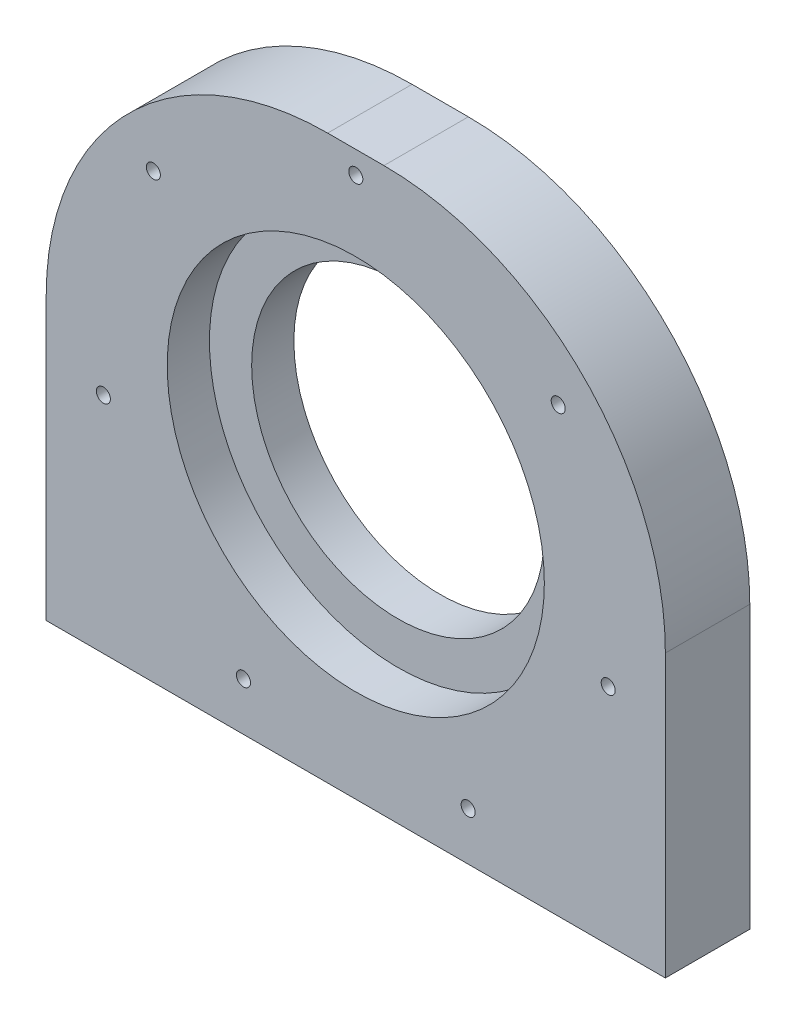
SolidWorks part; units mm, degrees
ref_plane "Ebene vorne" through (0, 0, 0) normal (0, 0, 1) x (1, 0, 0)
ref_plane "Ebene oben" through (0, 0, 0) normal (0, 1, 0) x (1, 0, 0)
ref_plane "Ebene rechts" through (0, 0, 0) normal (1, 0, 0) x (0, 0, -1)
sketch "Skizze1" plane through (0, 0, 0) normal (0, 0, 1) x (1, 0, 0)
  line L0 (0, 0) -> (110, 0)
  line L1 (110, 0) -> (110, 100)
  line L2 (110, 100) -> (0, 100)
  line L3 (0, 100) -> (0, 0)
  dimension "D1" = 110
  dimension "D2" = 100
extrude "Aufsatz-Linear austragen1" add sketch "Skizze1" along normal blind 15
sketch "Skizze2" plane through (0, 0, 15) normal (0, 0, 1) x (1, 0, 0)
  line L0 (0, 100) -> (110, 0) construction
  line L1 (0, 0) -> (110, 100) construction
  circle A0 centre (55, 50) radius 33.5
  dimension "D1" = 67
extrude "Schnitt-Linear austragen1" cut sketch "Skizze2" against normal blind 7.5
sketch "Skizze3" plane through (0, 0, 0) normal (0, 0, -1) x (-1, 0, 0)
  line L0 (-110, 100) -> (0, 0) construction
  line L1 (-110, 0) -> (0, 100) construction
  circle A0 centre (-55, 50) radius 26
  dimension "D1" = 52
extrude "Schnitt-Linear austragen2" cut sketch "Skizze3" against normal blind 7.5
sketch "Skizze4" plane through (0, 0, 0) normal (0, -1, 0) x (1, 0, 0)
  line L0 (0, 15) -> (110, 0) construction
  line L1 (0, 0) -> (110, 15) construction
  line L2 (55, 7.5) -> (-49945, 7.5) construction
  circle A0 centre (25, 7.5) radius 2.1
  circle A1 centre (85, 7.5) radius 2.1
  circle A2 centre (55, 7.5) radius 2.1
  point P10 (55, 7.5)
  dimension "D1" = 4.2
  dimension "D2" = 30
  dimension "D3" = 30
extrude "Schnitt-Linear austragen3" cut sketch "Skizze4" against normal blind 10
ref_plane "Ebene1" through (55, 0, 0) normal (1, 0, 0) x (0, 0, -1)
ref_plane "Ebene2" through (0, 0, 7.5) normal (0, 0, 1) x (1, 0, 0)
sketch "Skizze5" plane through (0, 0, 15) normal (0, 0, 1) x (1, 0, 0)
  line L0 (55, 0) -> (55, 50000) construction
  line L1 (0, 0) -> (110, 0) construction
  line L2 (0, 50) -> (55, 50) construction
  line L3 (0, 100) -> (0, 0) construction
  circle A0 centre (55, 96) radius 1.25
  circle A2 centre (90.9642, 78.6805) radius 1.25
  circle A3 centre (99.8467, 39.764) radius 1.25
  circle A4 centre (74.9587, 8.5554) radius 1.25
  circle A5 centre (35.0413, 8.5554) radius 1.25
  circle A6 centre (10.1533, 39.764) radius 1.25
  circle A7 centre (19.0358, 78.6805) radius 1.25
  point P4 (55, 0)
  point P9 (0, 50)
  dimension "D1" = 2.5
  dimension "D2" = 46
  dimension "D3" = 7
extrude "Schnitt-Linear austragen5" cut sketch "Skizze5" against normal blind 10
fillet "Verrundung1" radius 50 2 edges at (110, 100, 7.5) (0, 100, 7.5)
